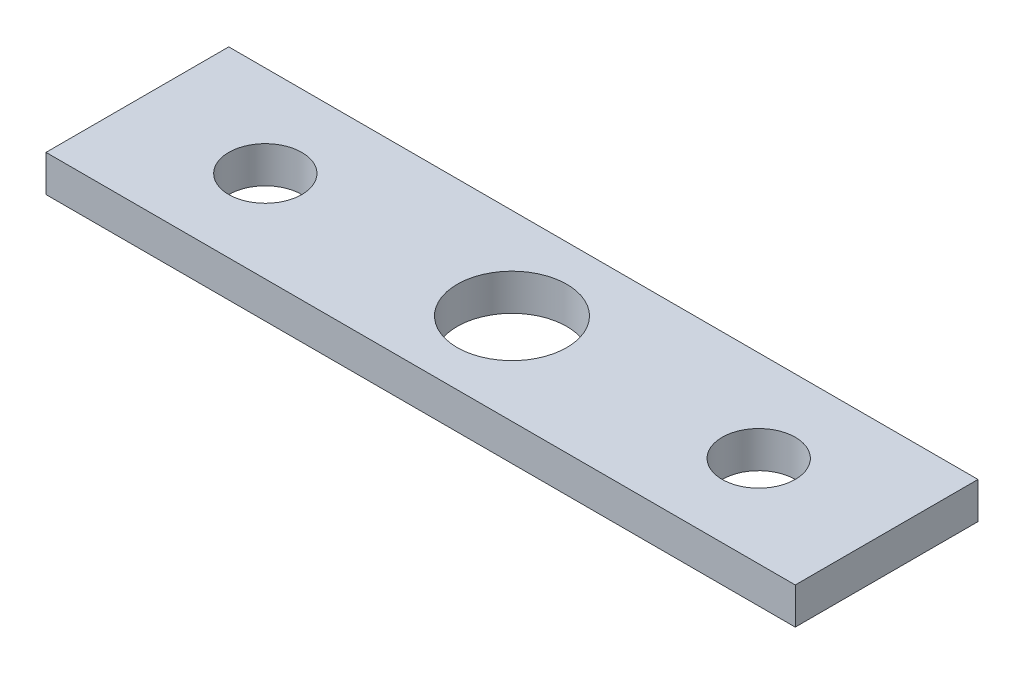
SolidWorks part; units mm, degrees
ref_plane "Front" through (0, 0, 0) normal (0, 0, 1) x (1, 0, 0)
ref_plane "Top" through (0, 0, 0) normal (0, 1, 0) x (1, 0, 0)
ref_plane "Right" through (0, 0, 0) normal (1, 0, 0) x (0, 0, -1)
sketch "Sketch1" plane through (0, 0, 0) normal (0, 1, 0) x (1, 0, 0)
  line L1 (0, 0) -> (35, 0)
  line L2 (0, 0) -> (0, 10)
  line L3 (0, 10) -> (35, 10)
  line L4 (35, 0) -> (35, 10)
  circle A0 centre (17.5, 5) radius 3
  dimension "D1" = 35
  dimension "D2" = 10
extrude "Boss-Extrude1" add sketch "Sketch1" along normal blind 2
sketch "Sketch4" plane through (0, 0, 0) normal (0, -1, 0) x (1, 0, 0)
  line L0 (0, -10) -> (0, 0) construction
  line L1 (35, 0) -> (35, -10) construction
  line L2 (0, 0) -> (35, 0) construction
  line L5 (0, 0) -> (35, 0) construction
  circle A0 centre (4, -5) radius 2
  circle A1 centre (31, -5) radius 2
  dimension "D1" = 4
  dimension "D2" = 4
  dimension "D3" = 5
  dimension "D4" = 5
extrude "Cut-Extrude2" cut sketch "Sketch4" against normal blind 20
sketch "Sketch5" plane through (0, 0, 0) normal (-1, 0, 0) x (0, 0, 1)
  line L1 (0, 2) -> (-10, 2)
  line L2 (0, 2) -> (0, 0)
  line L3 (0, 0) -> (-10, 0)
  line L4 (-10, 2) -> (-10, 0)
extrude "Boss-Extrude3" add sketch "Sketch5" along normal blind 3
sketch "Sketch6" plane through (35, 0, 0) normal (1, 0, 0) x (0, 0, -1)
  line L1 (0, 0) -> (10, 0)
  line L2 (0, 0) -> (0, 2)
  line L3 (0, 2) -> (10, 2)
  line L4 (10, 0) -> (10, 2)
extrude "Boss-Extrude4" add sketch "Sketch6" along normal blind 3
